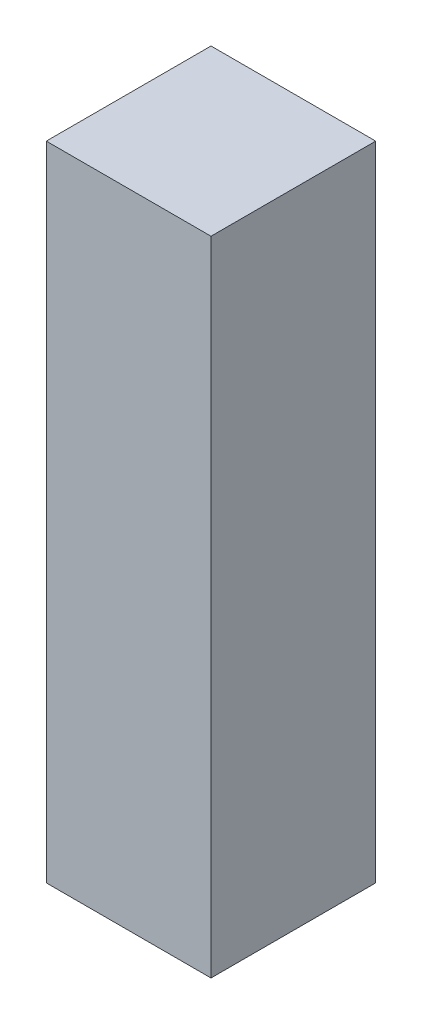
SolidWorks part; units mm, degrees
ref_plane "Front Plane" through (0, 0, 0) normal (0, 0, 1) x (1, 0, 0)
ref_plane "Top Plane" through (0, 0, 0) normal (0, 1, 0) x (1, 0, 0)
ref_plane "Right Plane" through (0, 0, 0) normal (1, 0, 0) x (0, 0, -1)
sketch "SK_P01_MicroFit3024posmated" plane through (0, 0, 0) normal (0, 1, 0) x (1, 0, 0)
  line L0 (-5, -5) -> (5, -5)
  line L1 (5, -5) -> (5, 5)
  line L2 (5, 5) -> (-5, 5)
  line L3 (-5, 5) -> (-5, -5)
extrude "P01_MicroFit3024posmated" add sketch "SK_P01_MicroFit3024posmated" along normal blind 39
